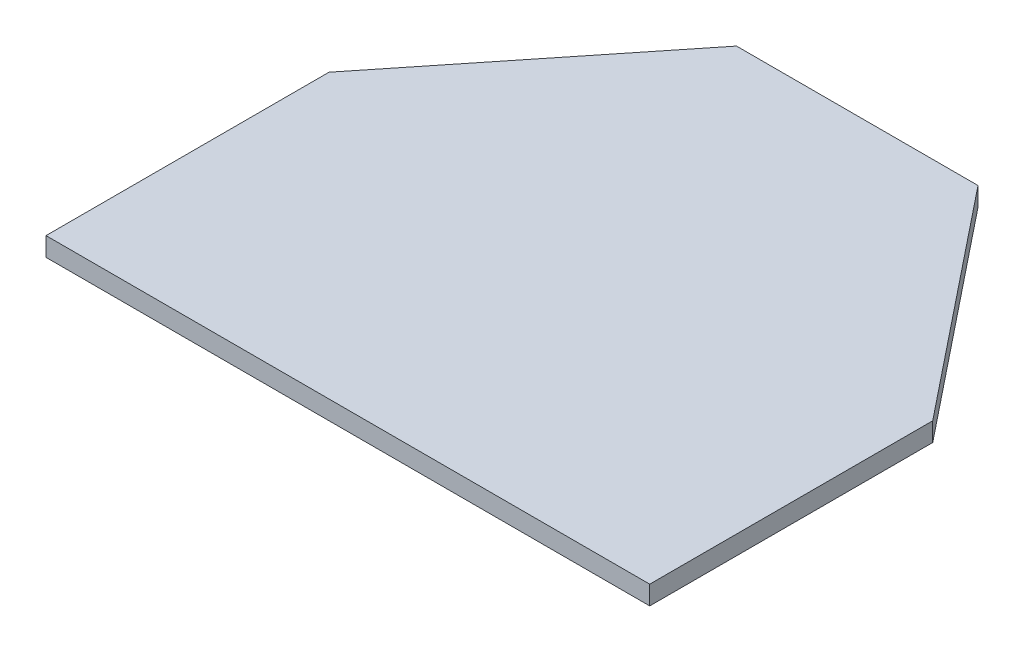
SolidWorks part; units mm, degrees
material "Nylon PA12"
ref_plane "Front Plane" through (0, 0, 0) normal (0, 0, 1) x (1, 0, 0)
ref_plane "Top Plane" through (0, 0, 0) normal (0, 1, 0) x (1, 0, 0)
ref_plane "Right Plane" through (0, 0, 0) normal (1, 0, 0) x (0, 0, -1)
sketch "Sketch1" plane through (0, 0, 0) normal (0, 1, 0) x (1, 0, 0)
  line L6 (-80, 0) -> (80, 0)
  line L7 (80, 0) -> (80, 75)
  line L8 (80, 75) -> (0, 175)
  line L9 (0, 175) -> (-80, 75)
  line L10 (-80, 75) -> (-80, 0)
  point P7 (0, 0)
  dimension "D1" = 160
  dimension "D2" = 75
  dimension "D3" = 175
  dimension "D4" = 75
extrude "Boss-Extrude1" add sketch "Sketch1" along normal mid plane 5
sketch "Sketch2" plane through (0, 0, 0) normal (0, 1, 0) x (1, 0, 0)
  line L6 (-175, 175) -> (175, 175)
  line L7 (-175, 175) -> (-175, 135)
  line L8 (-175, 135) -> (175, 135)
  line L9 (175, 175) -> (175, 135)
  point P1 (0, 175)
  dimension "D1" = 40
  dimension "D2" = 350
extrude "Cut-Extrude1" cut sketch "Sketch2" against normal through all both and the other way through all
